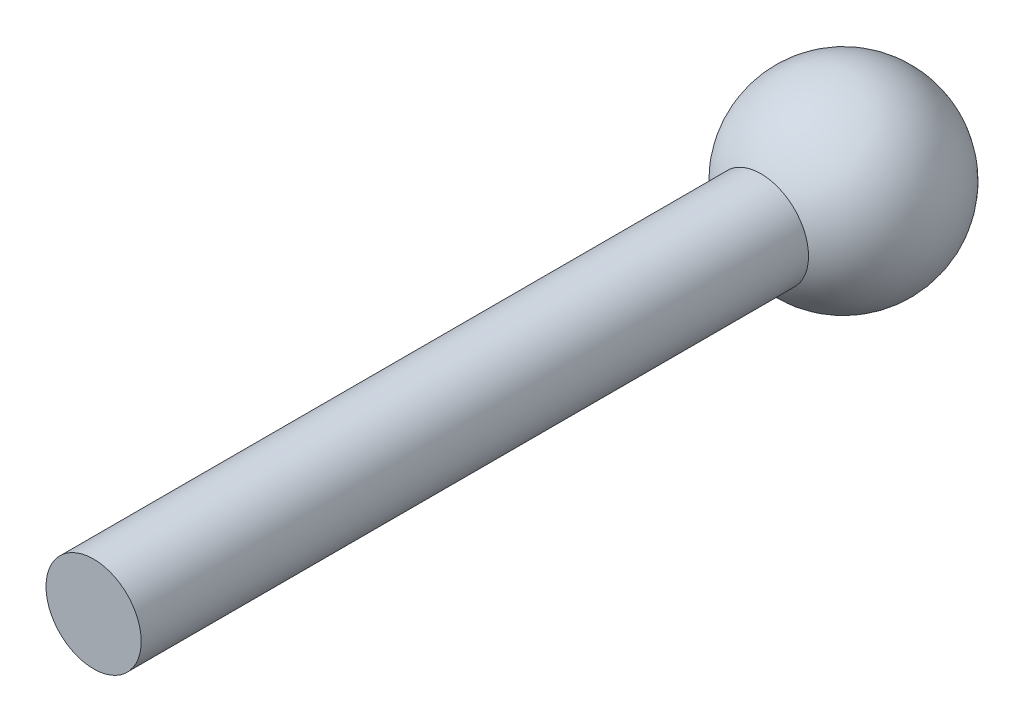
SolidWorks part; units mm, degrees
ref_plane "前视基准面" through (0, 0, 0) normal (0, 0, 1) x (1, 0, 0)
ref_plane "上视基准面" through (0, 0, 0) normal (0, 1, 0) x (1, 0, 0)
ref_plane "右视基准面" through (0, 0, 0) normal (1, 0, 0) x (0, 0, -1)
sketch "草图1" plane through (0, 0, 0) normal (0, 0, 1) x (1, 0, 0)
  circle A0 centre (0, 0) radius 5
  dimension "D1" = 10
extrude "凸台-拉伸1" add sketch "草图1" along normal blind 75
sketch "草图4" plane through (0, 0, 0) normal (0, 1, 0) x (1, 0, 0)
  line L0 (0, 13.7681) -> (0, -6.2319)
  arc A0 (0, -6.2319) -> (0, 13.7681) centre (0, 3.7681) ccw
  dimension "D1" = 20
revolve "旋转29" add sketch "草图4" angle 360 about L0
